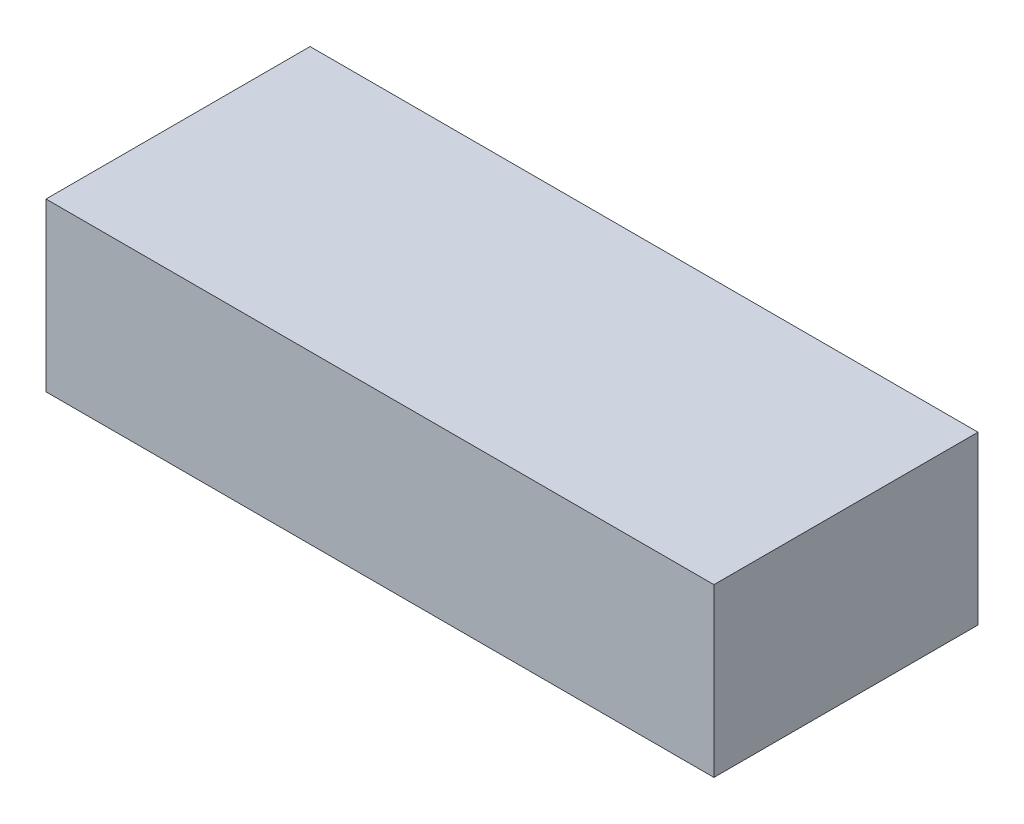
SolidWorks part; units mm, degrees
material "ABS"
ref_plane "Ön Düzlem" through (0, 0, 0) normal (0, 0, 1) x (1, 0, 0)
ref_plane "Üst Düzlem" through (0, 0, 0) normal (0, 1, 0) x (1, 0, 0)
ref_plane "Sağ Düzlem" through (0, 0, 0) normal (1, 0, 0) x (0, 0, -1)
sketch "Çizim1" plane through (0, 0, 0) normal (0, 1, 0) x (1, 0, 0)
  line L1 (-86, 34) -> (86, 34)
  line L2 (-86, 34) -> (-86, -34)
  line L3 (-86, -34) -> (86, -34)
  line L4 (86, 34) -> (86, -34)
  line L5 (-86, 34) -> (86, -34) construction
  line L6 (-86, -34) -> (86, 34) construction
  point P0 (0, 0)
  dimension "D1" = 68
  dimension "D2" = 172
extrude "Yükseklik-Ekstrüzyon1" add sketch "Çizim1" along normal mid plane 43
